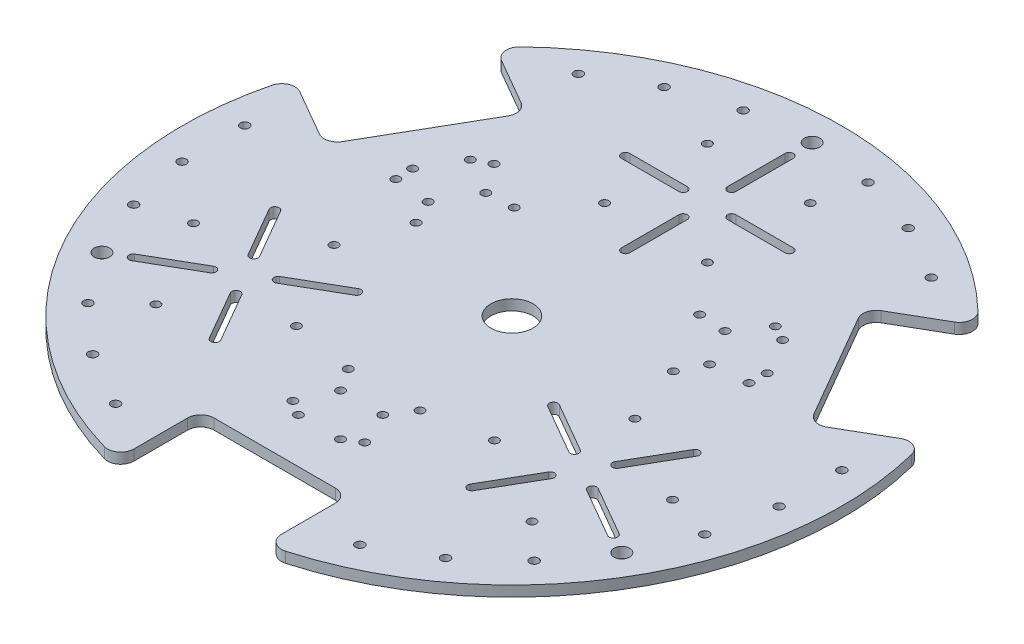
SolidWorks part; units mm, degrees
ref_plane "Front Plane" through (0, 0, 0) normal (0, 0, 1) x (1, 0, 0)
ref_plane "Top Plane" through (0, 0, 0) normal (0, 1, 0) x (1, 0, 0)
ref_plane "Right Plane" through (0, 0, 0) normal (1, 0, 0) x (0, 0, -1)
sketch "Sketch1" plane through (0, 0, 0) normal (0, 1, 0) x (1, 0, 0)
  line L0 (0, 0) -> (0, 125) construction
  line L1 (0, 0) -> (-17.3205, 10) construction
  line L2 (-89.4423, 25.0814) -> (-66.4423, 64.9186)
  line L3 (-68.2724, 71.7487) -> (-91.5024, 85.1605)
  line L4 (-96.2724, 23.2513) -> (-119.5024, 36.6631)
  line L5 (96.2724, 23.2513) -> (119.5024, 36.6631)
  line L6 (66.4423, 64.9186) -> (89.4423, 25.0814)
  line L7 (68.2724, 71.7487) -> (91.5024, 85.1605)
  line L8 (-28, -95) -> (-28, -121.8236)
  line L9 (23, -90) -> (-23, -90)
  line L10 (28, -95) -> (28, -121.8236)
  line L11 (-13.625, -48.465) -> (13.625, -48.465) construction
  line L12 (0, 0) -> (77.9423, 45) construction
  line L13 (0, 0) -> (-108.2532, -62.5) construction
  line L14 (-72.1832, -41.675) -> (-91.0626, -52.575) construction
  line L15 (-71.3832, -43.0606) -> (-90.2626, -53.9606)
  line L16 (-72.9832, -40.2894) -> (-91.8626, -51.1894)
  line L17 (-37.3257, -21.55) -> (-56.205, -32.45) construction
  line L18 (-36.5257, -22.9356) -> (-55.405, -33.8356)
  line L19 (-38.1257, -20.1644) -> (-57.005, -31.0644)
  line L20 (-72.1832, -41.675) -> (-56.205, -32.45) construction
  line L21 (-72.1832, -41.675) -> (-56.205, -32.45) construction
  line L22 (-68.8066, -29.0734) -> (-79.7066, -10.1941) construction
  line L23 (-70.1923, -29.8734) -> (-81.0923, -10.9941)
  line L24 (-67.421, -28.2734) -> (-78.321, -9.3941)
  line L25 (-56.205, -32.45) -> (-37.3257, -21.55) construction
  line L26 (-57.005, -31.0644) -> (-38.1257, -20.1644)
  line L27 (-55.405, -33.8356) -> (-36.5257, -22.9356)
  line L28 (-59.5816, -45.0516) -> (-48.6816, -63.9309) construction
  line L29 (-58.196, -44.2516) -> (-47.296, -63.1309)
  line L30 (-60.9673, -45.8516) -> (-50.0673, -64.7309)
  line L31 (0, 83.35) -> (0, 105.15) construction
  line L32 (-1.6, 83.35) -> (-1.6, 105.15)
  line L33 (1.6, 83.35) -> (1.6, 105.15)
  line L34 (0, 43.1) -> (0, 64.9) construction
  line L35 (-1.6, 43.1) -> (-1.6, 64.9)
  line L36 (1.6, 43.1) -> (1.6, 64.9)
  line L37 (9.225, 74.125) -> (31.025, 74.125) construction
  line L38 (9.225, 75.725) -> (31.025, 75.725)
  line L39 (9.225, 72.525) -> (31.025, 72.525)
  line L40 (-9.225, 74.125) -> (-31.025, 74.125) construction
  line L41 (-9.225, 72.525) -> (-31.025, 72.525)
  line L42 (-9.225, 75.725) -> (-31.025, 75.725)
  line L43 (72.1832, -41.675) -> (91.0626, -52.575) construction
  line L44 (72.9832, -40.2894) -> (91.8626, -51.1894)
  line L45 (71.3832, -43.0606) -> (90.2626, -53.9606)
  line L46 (37.3257, -21.55) -> (56.205, -32.45) construction
  line L47 (38.1257, -20.1644) -> (57.005, -31.0644)
  line L48 (36.5257, -22.9356) -> (55.405, -33.8356)
  line L49 (59.5816, -45.0516) -> (48.6816, -63.9309) construction
  line L50 (60.9673, -45.8516) -> (50.0673, -64.7309)
  line L51 (58.196, -44.2516) -> (47.296, -63.1309)
  line L52 (68.8066, -29.0734) -> (79.7066, -10.1941) construction
  line L53 (67.421, -28.2734) -> (78.321, -9.3941)
  line L54 (70.1923, -29.8734) -> (81.0923, -10.9941)
  line L55 (-49.8802, 55.605) -> (-73.0954, 15.395)
  line L56 (0, 0) -> (0, -90.0676) construction
  line L59 (13.625, -69.465) -> (-13.625, -69.465) construction
  line L60 (-13.625, -48.465) -> (-13.625, -69.465) construction
  line L61 (13.625, -48.465) -> (13.625, -69.465) construction
  line L62 (13.625, -71.065) -> (-13.625, -71.065) construction
  line L63 (8, -57) -> (-8, -57) construction
  line L64 (8, -57) -> (8, -73) construction
  line L65 (8, -73) -> (-8, -73) construction
  line L66 (-8, -57) -> (-8, -73) construction
  line L67 (8, -57) -> (-8, -73) construction
  line L68 (8, -73) -> (-8, -57) construction
  line L69 (8, -74.6) -> (-8, -74.6) construction
  circle A0 centre (0, 0) radius 8
  arc A1 (-119.5024, 36.6631) -> (-28, -121.8236) centre (0, 0) ccw
  circle A2 centre (0, 113.85) radius 2.95
  circle A3 centre (98.597, -56.925) radius 2.95
  circle A4 centre (-98.597, -56.925) radius 2.95
  circle A5 centre (0, 113.85) radius 1.675
  circle A6 centre (0, 0) radius 90 construction
  arc A7 (-89.4423, 25.0814) -> (-96.2724, 23.2513) centre (-93.7724, 27.5814) cw
  arc A8 (-66.4423, 64.9186) -> (-68.2724, 71.7487) centre (-70.7724, 67.4186) ccw
  arc A9 (89.4423, 25.0814) -> (96.2724, 23.2513) centre (93.7724, 27.5814) ccw
  arc A10 (66.4423, 64.9186) -> (68.2724, 71.7487) centre (70.7724, 67.4186) cw
  arc A11 (-23, -90) -> (-28, -95) centre (-23, -95) ccw
  arc A12 (23, -90) -> (28, -95) centre (23, -95) cw
  arc A13 (91.5024, 85.1605) -> (-91.5024, 85.1605) centre (0, 0) ccw
  arc A14 (28, -121.8236) -> (119.5024, 36.6631) centre (0, 0) ccw
  circle A15 centre (23.6707, 111.3621) radius 1.675
  circle A16 centre (46.307, 104.0072) radius 1.675
  circle A17 centre (66.9194, 92.1066) radius 1.675
  circle A18 centre (84.607, 76.1805) radius 1.675
  circle A19 centre (98.597, 56.925) radius 1.675
  circle A20 centre (108.2778, 35.1816) radius 1.675
  circle A21 centre (113.2263, 11.9006) radius 1.675
  circle A22 centre (113.2263, -11.9006) radius 1.675
  circle A23 centre (108.2778, -35.1816) radius 1.675
  circle A25 centre (84.607, -76.1805) radius 1.675
  circle A26 centre (66.9194, -92.1066) radius 1.675
  circle A27 centre (46.307, -104.0072) radius 1.675
  circle A28 centre (23.6707, -111.3621) radius 1.675
  circle A29 centre (0, -113.85) radius 1.675
  circle A30 centre (-23.6707, -111.3621) radius 1.675
  circle A31 centre (-46.307, -104.0072) radius 1.675
  circle A32 centre (-66.9194, -92.1066) radius 1.675
  circle A33 centre (-84.607, -76.1805) radius 1.675
  circle A35 centre (-108.2778, -35.1816) radius 1.675
  circle A36 centre (-113.2263, -11.9006) radius 1.675
  circle A37 centre (-113.2263, 11.9006) radius 1.675
  circle A38 centre (-108.2778, 35.1816) radius 1.675
  circle A39 centre (-98.597, 56.925) radius 1.675
  circle A40 centre (-84.607, 76.1805) radius 1.675
  circle A41 centre (-66.9194, 92.1066) radius 1.675
  circle A42 centre (-46.307, 104.0072) radius 1.675
  circle A43 centre (-23.6707, 111.3621) radius 1.675
  circle A44 centre (-98.597, -56.925) radius 1.675 [skipped]
  circle A45 centre (98.597, -56.925) radius 1.675 [skipped]
  circle A46 centre (0, 0) radius 106.75 construction
  arc A47 (-71.3832, -43.0606) -> (-72.9832, -40.2894) centre (-72.1832, -41.675) ccw
  arc A48 (-91.8626, -51.1894) -> (-90.2626, -53.9606) centre (-91.0626, -52.575) ccw
  circle A49 centre (0, 0) radius 66.5 construction
  arc A50 (-36.5257, -22.9356) -> (-38.1257, -20.1644) centre (-37.3257, -21.55) ccw
  arc A51 (-57.005, -31.0644) -> (-55.405, -33.8356) centre (-56.205, -32.45) ccw
  circle A52 centre (-64.1941, -37.0625) radius 2 construction
  arc A53 (-70.1923, -29.8734) -> (-67.421, -28.2734) centre (-68.8066, -29.0734) ccw
  arc A54 (-78.321, -9.3941) -> (-81.0923, -10.9941) centre (-79.7066, -10.1941) ccw
  arc A55 (-57.005, -31.0644) -> (-55.405, -33.8356) centre (-56.205, -32.45) ccw
  arc A56 (-36.5257, -22.9356) -> (-38.1257, -20.1644) centre (-37.3257, -21.55) ccw
  arc A57 (-58.196, -44.2516) -> (-60.9673, -45.8516) centre (-59.5816, -45.0516) ccw
  arc A58 (-50.0673, -64.7309) -> (-47.296, -63.1309) centre (-48.6816, -63.9309) ccw
  arc A59 (-1.6, 83.35) -> (1.6, 83.35) centre (0, 83.35) ccw
  arc A60 (1.6, 105.15) -> (-1.6, 105.15) centre (0, 105.15) ccw
  arc A61 (-1.6, 43.1) -> (1.6, 43.1) centre (0, 43.1) ccw
  arc A62 (1.6, 64.9) -> (-1.6, 64.9) centre (0, 64.9) ccw
  arc A63 (9.225, 75.725) -> (9.225, 72.525) centre (9.225, 74.125) ccw
  arc A64 (31.025, 72.525) -> (31.025, 75.725) centre (31.025, 74.125) ccw
  arc A65 (-9.225, 72.525) -> (-9.225, 75.725) centre (-9.225, 74.125) ccw
  arc A66 (-31.025, 75.725) -> (-31.025, 72.525) centre (-31.025, 74.125) ccw
  arc A67 (72.9832, -40.2894) -> (71.3832, -43.0606) centre (72.1832, -41.675) ccw
  arc A68 (90.2626, -53.9606) -> (91.8626, -51.1894) centre (91.0626, -52.575) ccw
  arc A69 (38.1257, -20.1644) -> (36.5257, -22.9356) centre (37.3257, -21.55) ccw
  arc A70 (55.405, -33.8356) -> (57.005, -31.0644) centre (56.205, -32.45) ccw
  arc A71 (60.9673, -45.8516) -> (58.196, -44.2516) centre (59.5816, -45.0516) ccw
  arc A72 (47.296, -63.1309) -> (50.0673, -64.7309) centre (48.6816, -63.9309) ccw
  arc A73 (67.421, -28.2734) -> (70.1923, -29.8734) centre (68.8066, -29.0734) ccw
  arc A74 (81.0923, -10.9941) -> (78.321, -9.3941) centre (79.7066, -10.1941) ccw
  circle A75 centre (0, 0) radius 100.95 construction
  circle A76 centre (-61.4878, 35.5) radius 5 construction
  circle A77 centre (-90.8316, -29.925) radius 1.6
  circle A78 centre (-57.0566, -10.425) radius 1.6
  circle A79 centre (-37.5566, -44.2) radius 1.6
  circle A80 centre (-71.3316, -63.7) radius 1.6
  circle A81 centre (19.5, 93.625) radius 1.6
  circle A82 centre (19.5, 54.625) radius 1.6
  circle A83 centre (-19.5, 54.625) radius 1.6
  circle A84 centre (-19.5, 93.625) radius 1.6
  circle A85 centre (71.3316, -63.7) radius 1.6
  circle A86 centre (37.5566, -44.2) radius 1.6
  circle A87 centre (57.0566, -10.425) radius 1.6
  circle A88 centre (90.8316, -29.925) radius 1.6
  circle A89 centre (0, 0) radius 69.465 construction
  circle A90 centre (-13.625, -48.465) radius 1.6
  circle A91 centre (13.625, -48.465) radius 1.6
  circle A92 centre (13.625, -69.465) radius 1.6
  circle A93 centre (-13.625, -69.465) radius 1.6
  circle A94 centre (-35.1594, 36.0321) radius 1.6
  circle A95 centre (-48.7844, 12.4329) radius 1.6
  circle A96 centre (-66.971, 22.9329) radius 1.6
  circle A97 centre (-53.346, 46.5321) radius 1.6
  circle A98 centre (48.7844, 12.4329) radius 1.6
  circle A99 centre (35.1594, 36.0321) radius 1.6
  circle A100 centre (53.346, 46.5321) radius 1.6
  circle A101 centre (66.971, 22.9329) radius 1.6
  circle A102 centre (0, 0) radius 73 construction
  circle A103 centre (-8, -73) radius 1.6
  circle A104 centre (-8, -57) radius 1.6
  circle A105 centre (8, -57) radius 1.6
  circle A106 centre (8, -73) radius 1.6
  circle A107 centre (-59.2199, 43.4282) radius 1.6
  circle A108 centre (-45.3634, 35.4282) radius 1.6
  circle A109 centre (-53.3634, 21.5718) radius 1.6
  circle A110 centre (-67.2199, 29.5718) radius 1.6
  circle A111 centre (67.2199, 29.5718) radius 1.6
  circle A112 centre (53.3634, 21.5718) radius 1.6
  circle A113 centre (45.3634, 35.4282) radius 1.6
  circle A114 centre (59.2199, 43.4282) radius 1.6
  point P14 (0, 0)
  point P18 (-77.9423, 45)
  point P22 (-91.9423, 20.7513)
  point P25 (-63.9423, 69.2487)
  point P44 (0, 0)
  point P84 (-81.6229, -47.125)
  point P103 (0, 0)
  point P115 (-46.7654, -27)
  point P129 (-74.2566, -19.6337)
  point P136 (-46.7654, -27)
  point P143 (-54.1316, -54.4913)
  point P148 (-64.1941, -37.0625)
  point P150 (0, 94.25)
  point P157 (0, 54)
  point P164 (20.125, 74.125)
  point P171 (-20.125, 74.125)
  point P178 (81.6229, -47.125)
  point P185 (46.7654, -27)
  point P192 (54.1316, -54.4913)
  point P199 (74.2566, -19.6337)
  point P204 (0, 0)
  point P209 (-61.4878, 35.5)
  point P220 (-64.1941, -37.0625)
  point P237 (0, 0)
  point P245 (0, -65)
  point P264 (0, 0)
  point P295 (0, 0)
  dimension "D1" = 250
  dimension "D2" = 16
  dimension "D3" = 113.85
  dimension "D4" = 3
  dimension "D5" = 3.35
  dimension "D6" = 60
  dimension "D8" = 5
  dimension "D12" = 213.5
  dimension "D13" = 3.2
  dimension "D14" = 21.8
  dimension "D15" = 3.2
  dimension "D16" = 133
  dimension "D18" = 4
  dimension "D20" = 19
  dimension "D21" = 3.2
  dimension "D26" = 138.93
  dimension "D28" = 3.2
  dimension "D31" = 90
  dimension "D32" = 146
  dimension "D35" = 3.2
  dimension "D37" = 3
  dimension "D7" = 56
  dimension "D11" = 60
  dimension "D17" = 21.8
  dimension "D22" = 17.9
  dimension "D23" = 17.9
  dimension "D27" = 21
  dimension "D29" = 27.25
  dimension "D33" = 16
  dimension "D34" = 16
  dimension "D36" = 15.4
  dimension "D9" = 3
  dimension "D10" = 30
  dimension "D19" = 3
  dimension "D24" = 4
  dimension "D25" = 3
  dimension "D30" = 3
extrude "Boss-Extrude2" add sketch "Sketch1" along normal blind 4
fillet "Fillet1" radius 5 6 edges at (91.5024, 2, -85.1605) (119.5024, 2, -36.6631) (28, 2, 121.8236) (-28, 2, 121.8236) (-119.5024, 2, -36.6631) (-91.5024, 2, -85.1605)
